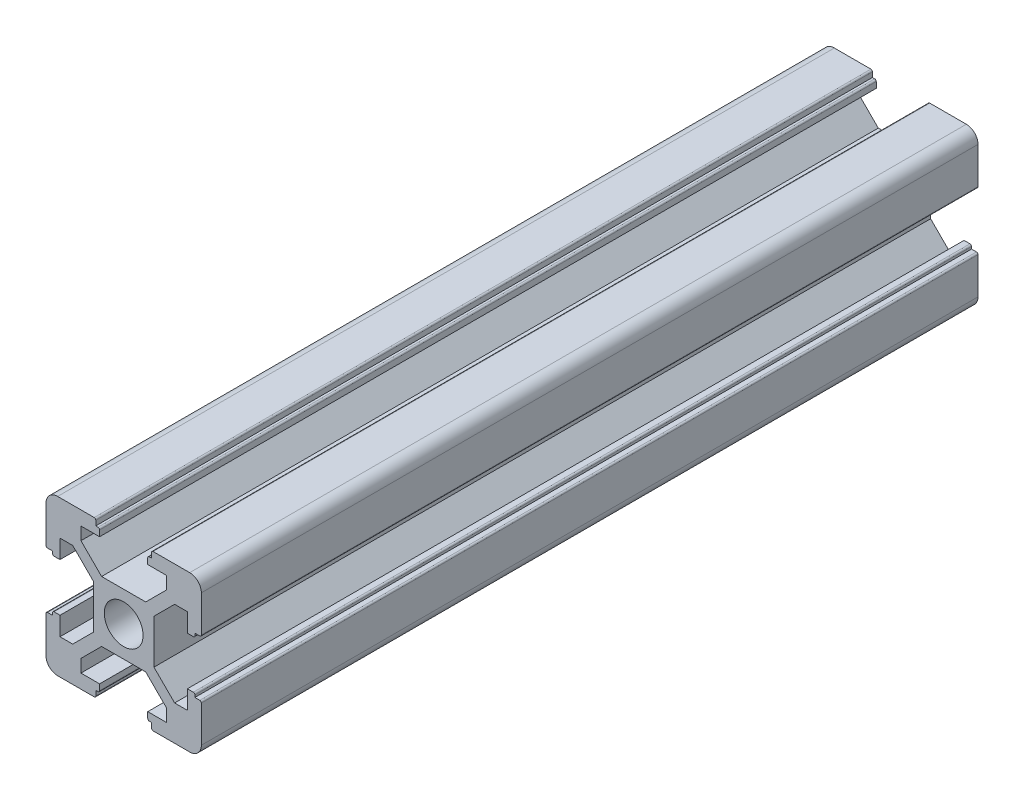
SolidWorks part; units mm, degrees
ref_plane "前视基准面" through (0, 0, 0) normal (0, 0, 1) x (1, 0, 0)
ref_plane "上视基准面" through (0, 0, 0) normal (0, 1, 0) x (1, 0, 0)
ref_plane "右视基准面" through (0, 0, 0) normal (1, 0, 0) x (0, 0, -1)
sketch "草图1" plane through (0, 0, 0) normal (0, 0, 1) x (1, 0, 0)
  line L0 (2.8393, 3.9) -> (5.5, 6.5607)
  line L1 (10, -3.7898) -> (10, -8.5)
  line L2 (3.7898, -10) -> (8.5, -10)
  line L3 (3.7898, 10) -> (8.5, 10)
  line L4 (10, 3.7898) -> (10, 8.5)
  line L5 (-10, -10) -> (-9.5607, -9.5607) construction
  line L6 (3.5898, -9.1655) -> (3.5898, -9.8)
  line L7 (-2.8393, -3.9) -> (2.8393, -3.9)
  line L8 (-3.9, -2.8393) -> (-3.9, 2.8393)
  line L9 (-2.8393, 3.9) -> (2.8393, 3.9)
  line L10 (3.9, -2.8393) -> (3.9, 2.8393)
  line L11 (3.3, -9.1655) -> (3.5898, -9.1655)
  line L12 (9.5607, 9.5607) -> (10, 10) construction
  line L13 (5.5, 6.5607) -> (5.5, 8.2)
  line L14 (5.5, 8.2) -> (3.1, 8.2)
  line L15 (3.1, 8.2) -> (3.1, 8.9655)
  line L16 (3.3, 9.1655) -> (3.5898, 9.1655)
  line L17 (3.5898, 9.1655) -> (3.5898, 9.8)
  line L18 (6.5607, 5.5) -> (8.2, 5.5)
  line L19 (3.9, 2.8393) -> (6.5607, 5.5)
  line L20 (9.1655, 3.5898) -> (9.8, 3.5898)
  line L21 (9.1655, 3.3) -> (9.1655, 3.5898)
  line L22 (8.2, 3.1) -> (8.9655, 3.1)
  line L23 (8.2, 5.5) -> (8.2, 3.1)
  line L24 (3.1, -8.2) -> (3.1, -8.9655)
  line L25 (5.5, -8.2) -> (3.1, -8.2)
  line L26 (5.5, -6.5607) -> (5.5, -8.2)
  line L27 (2.8393, -3.9) -> (5.5, -6.5607)
  line L28 (6.5607, -5.5) -> (8.2, -5.5)
  line L29 (3.9, -2.8393) -> (6.5607, -5.5)
  line L30 (8.2, -3.1) -> (8.9655, -3.1)
  line L31 (9.1655, -3.5898) -> (9.8, -3.5898)
  line L32 (9.1655, -3.3) -> (9.1655, -3.5898)
  line L33 (8.2, -5.5) -> (8.2, -3.1)
  line L34 (-3.7898, -10) -> (-8.5, -10)
  line L35 (-10, -3.7898) -> (-10, -8.5)
  line L36 (-9.1655, -3.5898) -> (-9.8, -3.5898)
  line L37 (-9.1655, -3.3) -> (-9.1655, -3.5898)
  line L38 (-8.2, -3.1) -> (-8.9655, -3.1)
  line L39 (-8.2, -5.5) -> (-8.2, -3.1)
  line L40 (-6.5607, -5.5) -> (-8.2, -5.5)
  line L41 (-3.9, -2.8393) -> (-6.5607, -5.5)
  line L42 (-5.5, -6.5607) -> (-5.5, -8.2)
  line L43 (-2.8393, -3.9) -> (-5.5, -6.5607)
  line L44 (-3.1, -8.2) -> (-3.1, -8.9655)
  line L45 (-3.5898, -9.1655) -> (-3.5898, -9.8)
  line L46 (-3.3, -9.1655) -> (-3.5898, -9.1655)
  line L47 (-5.5, -8.2) -> (-3.1, -8.2)
  line L48 (-10, 3.7898) -> (-10, 8.5)
  line L49 (-3.7898, 10) -> (-8.5, 10)
  line L50 (-3.5898, 9.1655) -> (-3.5898, 9.8)
  line L51 (-3.3, 9.1655) -> (-3.5898, 9.1655)
  line L52 (-3.1, 8.2) -> (-3.1, 8.9655)
  line L53 (-5.5, 8.2) -> (-3.1, 8.2)
  line L54 (-5.5, 6.5607) -> (-5.5, 8.2)
  line L55 (-2.8393, 3.9) -> (-5.5, 6.5607)
  line L56 (-6.5607, 5.5) -> (-8.2, 5.5)
  line L57 (-3.9, 2.8393) -> (-6.5607, 5.5)
  line L58 (-8.2, 3.1) -> (-8.9655, 3.1)
  line L59 (-9.1655, 3.5898) -> (-9.8, 3.5898)
  line L60 (-9.1655, 3.3) -> (-9.1655, 3.5898)
  line L61 (-8.2, 5.5) -> (-8.2, 3.1)
  circle A0 centre (0, 0) radius 2.5
  arc A1 (9.8, 3.5898) -> (10, 3.7898) centre (9.8, 3.7898) ccw
  arc A2 (10, -8.5) -> (8.5, -10) centre (8.5, -8.5) cw
  arc A3 (8.5, 10) -> (10, 8.5) centre (8.5, 8.5) cw
  arc A4 (3.5898, -9.8) -> (3.7898, -10) centre (3.7898, -9.8) ccw
  arc A5 (9.1655, 3.3) -> (8.9655, 3.1) centre (8.9655, 3.3) cw
  arc A6 (3.1, 8.9655) -> (3.3, 9.1655) centre (3.3, 8.9655) cw
  arc A7 (3.5898, 9.8) -> (3.7898, 10) centre (3.7898, 9.8) cw
  arc A8 (3.3, -9.1655) -> (3.1, -8.9655) centre (3.3, -8.9655) cw
  arc A9 (8.9655, -3.1) -> (9.1655, -3.3) centre (8.9655, -3.3) cw
  arc A10 (9.8, -3.5898) -> (10, -3.7898) centre (9.8, -3.7898) cw
  arc A11 (-8.5, -10) -> (-10, -8.5) centre (-8.5, -8.5) cw
  arc A12 (-9.8, -3.5898) -> (-10, -3.7898) centre (-9.8, -3.7898) ccw
  arc A13 (-9.1655, -3.3) -> (-8.9655, -3.1) centre (-8.9655, -3.3) cw
  arc A14 (-3.1, -8.9655) -> (-3.3, -9.1655) centre (-3.3, -8.9655) cw
  arc A15 (-3.5898, -9.8) -> (-3.7898, -10) centre (-3.7898, -9.8) cw
  arc A16 (-10, 8.5) -> (-8.5, 10) centre (-8.5, 8.5) cw
  arc A17 (-3.5898, 9.8) -> (-3.7898, 10) centre (-3.7898, 9.8) ccw
  arc A18 (-3.3, 9.1655) -> (-3.1, 8.9655) centre (-3.3, 8.9655) cw
  arc A19 (-8.9655, 3.1) -> (-9.1655, 3.3) centre (-8.9655, 3.3) cw
  arc A20 (-9.8, 3.5898) -> (-10, 3.7898) centre (-9.8, 3.7898) cw
  point P0 (0, 0)
  point P9 (10, 3.5898)
  point P17 (0, 0)
  point P40 (9.1655, 3.1)
  point P43 (3.1, 9.1655)
  point P46 (3.5898, 10)
  point P69 (0, 0)
  point P95 (0, 0)
  point P121 (0, 0)
  dimension "D1" = 5
  dimension "D11" = 0.2
  dimension "D12" = 0.2
  dimension "D2" = 0.2
  dimension "D3" = 4
  dimension "D7" = 1.5
  dimension "D8" = 3.1
  dimension "D9" = 5.5
  dimension "D10" = 1.8
extrude "凸台-拉伸1" add sketch "草图1" along normal blind 100
